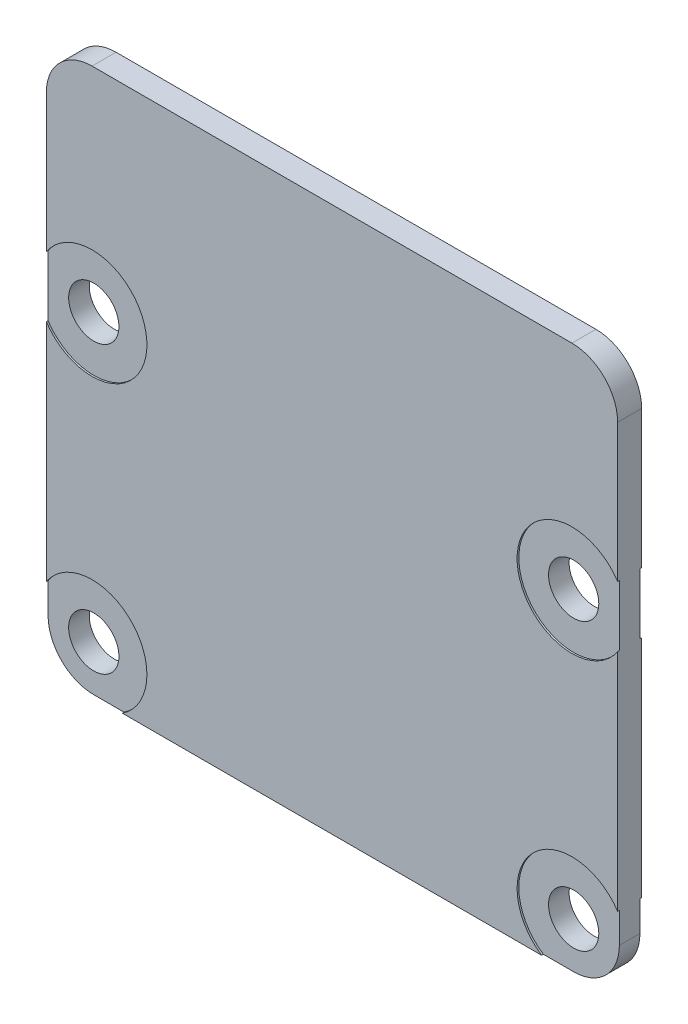
SolidWorks part; units mm, degrees
ref_plane "Front Plane" through (0, 0, 0) normal (0, 0, 1) x (1, 0, 0)
ref_plane "Top Plane" through (0, 0, 0) normal (0, 1, 0) x (1, 0, 0)
ref_plane "Right Plane" through (0, 0, 0) normal (1, 0, 0) x (0, 0, -1)
sketch "Sketch2" plane through (0, 0, 0) normal (0, 0, 1) x (1, 0, 0)
  line L1 (-4.25, 4.25) -> (4.25, 4.25) construction
  line L2 (-4.25, 4.25) -> (-4.25, -4.25) construction
  line L3 (-4.25, -4.25) -> (4.25, -4.25) construction
  line L4 (4.25, 4.25) -> (4.25, -4.25) construction
  line L5 (-4.25, 4.25) -> (4.25, -4.25) construction
  line L6 (-4.25, -4.25) -> (4.25, 4.25) construction
  line L7 (-12.5, 9.462) -> (12.5, 9.462) construction
  line L8 (-12.5, 9.462) -> (-12.5, -14.4) construction
  line L9 (-12.5, -14.4) -> (12.5, -14.4) construction
  line L10 (12.5, 9.462) -> (12.5, -14.4) construction
  line L11 (-2.81, -11.19) -> (5.41, -11.19) construction
  line L12 (-2.81, -11.19) -> (-2.81, -8.21) construction
  line L13 (-2.81, -8.21) -> (5.41, -8.21) construction
  line L14 (5.41, -11.19) -> (5.41, -8.21) construction
  line L15 (-2.81, -11.19) -> (5.41, -8.21) construction
  line L16 (-2.81, -8.21) -> (5.41, -11.19) construction
  line L17 (-10.5, 0.1) -> (10.5, 0.1) construction
  line L18 (-10.5, 0.1) -> (-10.5, -12.4) construction
  line L19 (-10.5, -12.4) -> (10.5, -12.4) construction
  line L20 (10.5, 0.1) -> (10.5, -12.4) construction
  circle A0 centre (-10.5, 0.1) radius 1.1 construction
  circle A1 centre (10.5, 0.1) radius 1.1 construction
  circle A2 centre (10.5, -12.4) radius 1.1 construction
  circle A3 centre (-10.5, -12.4) radius 1.1 construction
  point P0 (0, 0)
  point P10 (1.3, -9.7)
  dimension "D14" = 2.2
  dimension "D1" = 8.5
  dimension "D2" = 23.862
  dimension "D3" = 25
  dimension "D4" = 12.5
  dimension "D5" = 9.462
  dimension "D6" = 4.7
  dimension "D7" = 13.8
  dimension "D8" = 8.22
  dimension "D9" = 2.98
  dimension "D10" = 2
  dimension "D11" = 2
  dimension "D12" = 2
  dimension "D13" = 14.5
sketch "Sketch3" plane through (0, 0, 0) normal (0, 0, 1) x (1, 0, 0)
  line L0 (-12.5, -14.4) -> (12.5, -14.4) construction
  line L1 (-12.5, 9.462) -> (-12.5, -14.4) construction
  line L2 (12.5, 9.462) -> (12.5, -14.4) construction
  line L3 (-12.5, 9.462) -> (12.5, 9.462) construction
  line L4 (-12.5, -14.4) -> (12.5, -14.4)
  line L5 (-12.5, 9.462) -> (-12.5, -14.4)
  line L6 (12.5, 9.462) -> (12.5, -14.4)
  line L7 (-12.5, 9.462) -> (12.5, 9.462)
extrude "Boss-Extrude1" add sketch "Sketch3" against normal blind 0.9
fillet "Fillet1" radius 2 4 edges at (-12.5, -14.4, -0.45) (12.5, -14.4, -0.45) (-12.5, 9.462, -0.45) (12.5, 9.462, -0.45)
sketch "Sketch4" plane through (0, 0, 0) normal (0, 0, 1) x (1, 0, 0)
  circle A0 centre (-10.5, 0.1) radius 1.1 construction
  circle A1 centre (-10.5, -12.4) radius 1.1 construction
  circle A2 centre (10.5, -12.4) radius 1.1 construction
  circle A3 centre (10.5, 0.1) radius 1.1 construction
  circle A4 centre (-10.5, 0.1) radius 1.1
  circle A5 centre (-10.5, -12.4) radius 1.1
  circle A6 centre (10.5, -12.4) radius 1.1
  circle A7 centre (10.5, 0.1) radius 1.1
extrude "Cut-Extrude1" cut sketch "Sketch4" against normal through all
sketch "Sketch5" plane through (0, 0, 0) normal (0, 0, 1) x (1, 0, 0)
  line L0 (12.5, 1.4266) -> (12.5, 7.462)
  line L1 (-12.5, -1.2266) -> (-12.5, -11.0734)
  line L4 (-12.5, 7.462) -> (-12.5, -12.4)
  line L5 (-10.5, -14.4) -> (10.5, -14.4)
  line L6 (12.5, -12.4) -> (12.5, 7.462)
  line L7 (10.5, 9.462) -> (-10.5, 9.462)
  line L8 (-12.5, 7.462) -> (-12.5, 1.4266)
  line L9 (-9.1734, -14.4) -> (9.1734, -14.4)
  line L10 (12.5, -11.0734) -> (12.5, -1.2266)
  line L11 (10.5, 9.462) -> (-10.5, 9.462)
  arc A0 (12.5, 1.4266) -> (12.5, -1.2266) centre (10.5, 0.1) ccw
  arc A1 (-12.5, -1.2266) -> (-12.5, 1.4266) centre (-10.5, 0.1) ccw
  arc A2 (-9.1734, -14.4) -> (-12.5, -11.0734) centre (-10.5, -12.4) ccw
  arc A3 (12.5, -11.0734) -> (9.1734, -14.4) centre (10.5, -12.4) ccw
  arc A4 (-12.5, -12.4) -> (-10.5, -14.4) centre (-10.5, -12.4) ccw
  arc A5 (10.5, -14.4) -> (12.5, -12.4) centre (10.5, -12.4) ccw
  arc A6 (12.5, 7.462) -> (10.5, 9.462) centre (10.5, 7.462) ccw
  arc A7 (-10.5, 9.462) -> (-12.5, 7.462) centre (-10.5, 7.462) ccw
  arc A10 (12.5, 7.462) -> (10.5, 9.462) centre (10.5, 7.462) ccw
  arc A11 (-10.5, 9.462) -> (-12.5, 7.462) centre (-10.5, 7.462) ccw
  dimension "D2" = 4.8
  dimension "D1" = 0
extrude "Boss-Extrude2" add sketch "Sketch5" along normal blind 0.075
sketch "Sketch6" plane through (0, 0, -0.9) normal (0, 0, -1) x (-1, 0, 0)
  line L6 (12.5, 1.4266) -> (12.5, 7.462)
  line L7 (12.5, -11.0734) -> (12.5, -1.2266)
  line L8 (-9.1734, -14.4) -> (9.1734, -14.4)
  line L9 (-12.5, -1.2266) -> (-12.5, -11.0734)
  line L10 (-12.5, 7.462) -> (-12.5, 1.4266)
  line L11 (10.5, 9.462) -> (-10.5, 9.462)
  line L12 (12.5, 1.4266) -> (12.5, 7.462)
  line L13 (12.5, -11.0734) -> (12.5, -1.2266)
  line L14 (-9.1734, -14.4) -> (9.1734, -14.4)
  line L15 (-12.5, -1.2266) -> (-12.5, -11.0734)
  line L16 (-12.5, 7.462) -> (-12.5, 1.4266)
  line L17 (10.5, 9.462) -> (-10.5, 9.462)
  arc A6 (12.5, 7.462) -> (10.5, 9.462) centre (10.5, 7.462) ccw
  arc A7 (12.5, 1.4266) -> (12.5, -1.2266) centre (10.5, 0.1) ccw
  arc A8 (12.5, -11.0734) -> (9.1734, -14.4) centre (10.5, -12.4) ccw
  arc A9 (-9.1734, -14.4) -> (-12.5, -11.0734) centre (-10.5, -12.4) ccw
  arc A10 (-12.5, -1.2266) -> (-12.5, 1.4266) centre (-10.5, 0.1) ccw
  arc A11 (-10.5, 9.462) -> (-12.5, 7.462) centre (-10.5, 7.462) ccw
  arc A12 (12.5, 7.462) -> (10.5, 9.462) centre (10.5, 7.462) ccw
  arc A13 (12.5, 1.4266) -> (12.5, -1.2266) centre (10.5, 0.1) ccw
  arc A14 (12.5, -11.0734) -> (9.1734, -14.4) centre (10.5, -12.4) ccw
  arc A15 (-9.1734, -14.4) -> (-12.5, -11.0734) centre (-10.5, -12.4) ccw
  arc A16 (-12.5, -1.2266) -> (-12.5, 1.4266) centre (-10.5, 0.1) ccw
  arc A17 (-10.5, 9.462) -> (-12.5, 7.462) centre (-10.5, 7.462) ccw
  dimension "D1" = 0
extrude "Boss-Extrude3" add sketch "Sketch6" along normal blind 0.075
sketch "Sketch7" plane through (0, 0, 0.075) normal (0, 0, 1) x (1, 0, 0)
  line L0 (-2.81, -11.19) -> (-2.81, -8.21) construction
  line L1 (5.41, -11.19) -> (5.41, -8.21) construction
  line L2 (-2.81, -8.21) -> (5.41, -11.19) construction
  line L3 (-2.81, -11.19) -> (5.41, -8.21) construction
  line L4 (-2.81, -8.21) -> (5.41, -8.21) construction
  line L5 (-2.81, -11.19) -> (5.41, -11.19) construction
  line L6 (-2.81, -11.19) -> (-2.81, -8.21) construction
  line L7 (5.41, -11.19) -> (5.41, -8.21) construction
  line L8 (-2.81, -8.21) -> (5.41, -11.19) construction
  line L9 (-2.81, -11.19) -> (5.41, -8.21) construction
  line L10 (-2.81, -8.21) -> (5.41, -8.21) construction
  line L11 (-2.81, -11.19) -> (5.41, -11.19) construction
  point P0 (1.3, -9.7)
  point P6 (0, 0)
sketch "Sketch9" plane through (0, 0, 0) normal (0, 1, 0) x (1, 0, 0)
  line L0 (0, 0) -> (0, -17.1807) construction
